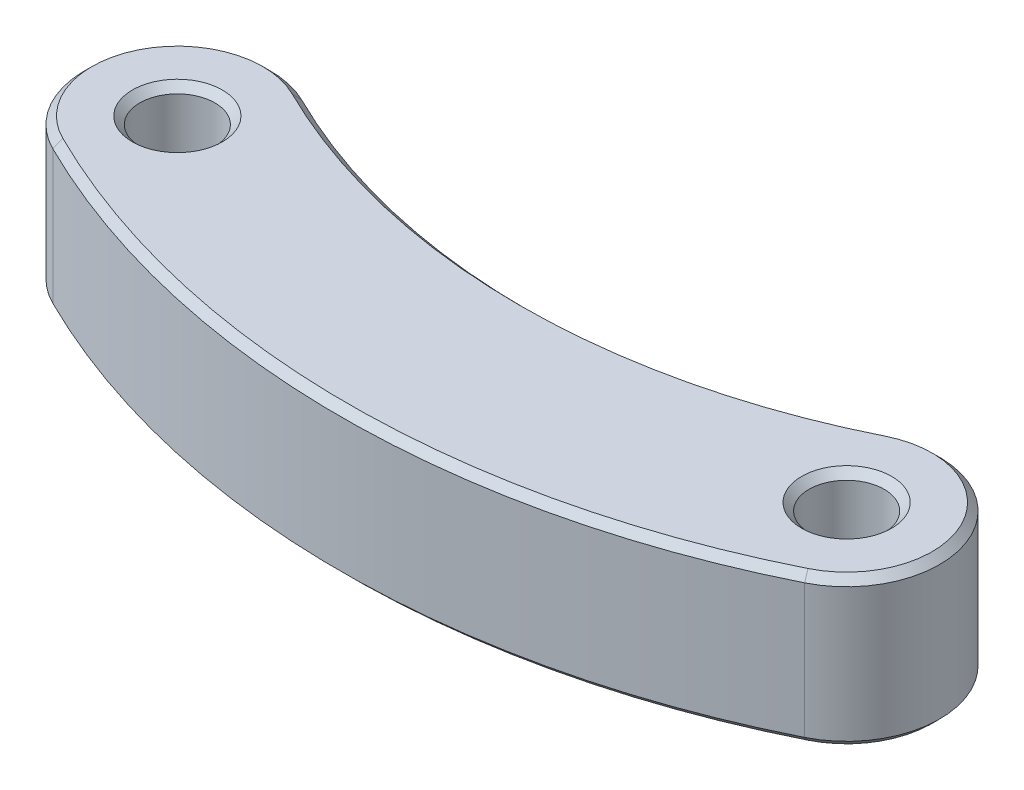
SolidWorks part; units mm, degrees
ref_plane "Front Plane" through (0, 0, 0) normal (0, 0, 1) x (1, 0, 0)
ref_plane "Top Plane" through (0, 0, 0) normal (0, 1, 0) x (1, 0, 0)
ref_plane "Right Plane" through (0, 0, 0) normal (1, 0, 0) x (0, 0, -1)
sketch "Sketch1" plane through (0, 0, 0) normal (0, 1, 0) x (1, 0, 0)
  line L0 (-4.5, 0) -> (4.5, 0) construction
  line L1 (-3.9446, 1.1198) -> (-5.0554, -1.1198) construction
  line L2 (3.9446, 1.1198) -> (5.0554, -1.1198) construction
  arc A0 (-3.9446, 1.1198) -> (-5.0554, -1.1198) centre (-4.5, 0) ccw
  arc A1 (5.0554, -1.1198) -> (3.9446, 1.1198) centre (4.5, 0) ccw
  circle A2 centre (-4.5, 0) radius 0.505
  circle A3 centre (4.5, 0) radius 0.505
  arc A4 (-3.9446, 1.1198) -> (3.9446, 1.1198) centre (0, 9.0724) ccw
  arc A5 (-5.0554, -1.1198) -> (5.0554, -1.1198) centre (0, 9.0724) ccw
  point P3 (0, 0)
  point P12 (0, 0)
  dimension "D3" = 1.01
  dimension "D2" = 1.25
  dimension "D1" = 9
extrude "Boss-Extrude1" add sketch "Sketch1" along normal mid plane 2
sketch "Sketch2" plane through (0, 0, 0) normal (0, 1, 0) x (1, 0, 0)
  circle A0 centre (-4.5, 0) radius 0.75
  circle A1 centre (4.5, 0) radius 0.75
  circle A2 centre (-4.5, 0) radius 0.505
  circle A3 centre (4.5, 0) radius 0.505
  circle A4 centre (4.5, 0) radius 0.505 construction
  dimension "D1" = 1.5
extrude "Boss-Extrude2" [suppressed] add sketch "Sketch2" along normal mid plane 2.5
fillet "Fillet2" [suppressed] radius 0.5
chamfer "Chamfer1" distance 0.1 angle 45 8 edges at (0, 1, -0.1953) (-5.6198, 1, -0.5554) (5.6198, 1, -0.5554) (0, 1, 2.3047) (0, -1, -0.1953) (-5.6198, -1, -0.5554) (5.6198, -1, -0.5554) (0, -1, 2.3047)
chamfer "Chamfer2" distance 0.1 angle 45 4 edges at (-4.5, 1, 0.505) (4.5, 1, 0.505) (4.5, -1, 0.505) (-4.5, -1, 0.505)
